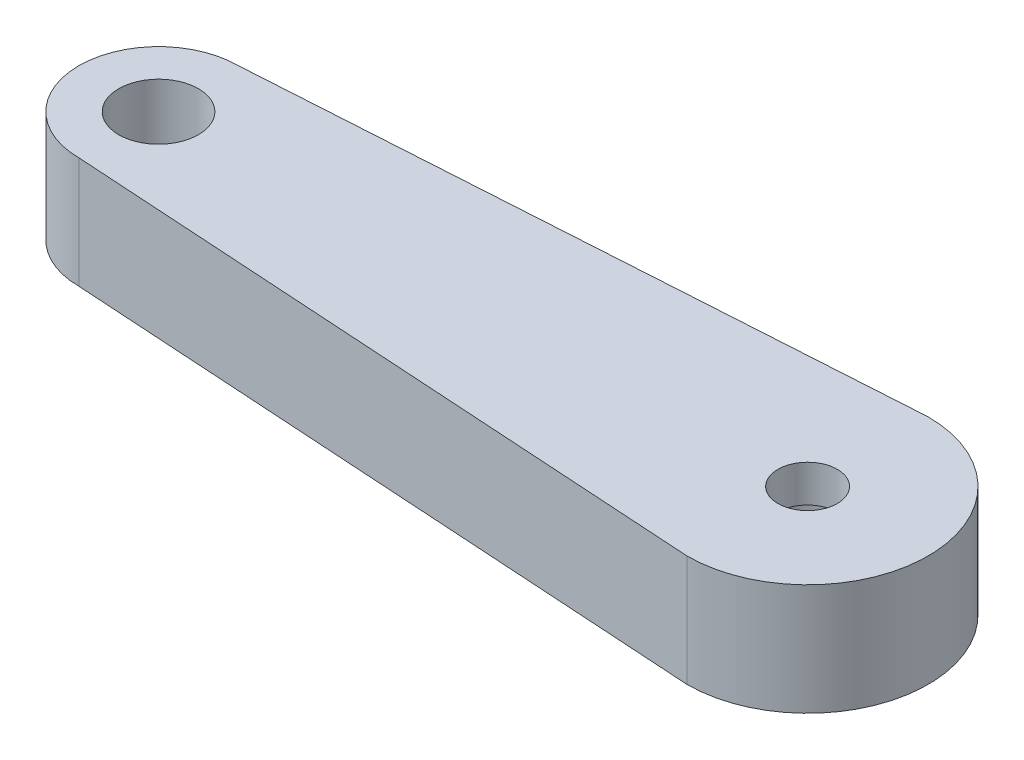
SolidWorks part; units mm, degrees
ref_plane "Front Plane" through (0, 0, 0) normal (0, 0, 1) x (1, 0, 0)
ref_plane "Top Plane" through (0, 0, 0) normal (0, 1, 0) x (1, 0, 0)
ref_plane "Right Plane" through (0, 0, 0) normal (1, 0, 0) x (0, 0, -1)
sketch "Sketch1" plane through (0, 0, 0) normal (0, 1, 0) x (1, 0, 0)
  line L0 (0, 0) -> (0, 6.5) construction
  line L1 (0, 0) -> (0, -6.5) construction
  line L2 (0, 0) -> (-35, 0) construction
  line L3 (-35, 0) -> (-35, 4.3) construction
  line L4 (-35, 0) -> (-35, -4.3) construction
  line L5 (-35, 4.3) -> (0, 6.5)
  line L6 (-35, -4.3) -> (0, -6.5)
  arc A1 (0, 6.5) -> (0, -6.5) centre (0, 0) cw
  arc A3 (-35, 4.3) -> (-35, -4.3) centre (-35, 0) ccw
  dimension "D4" = 4.3
  dimension "D5" = 4.3
  dimension "D1" = 6.5
  dimension "D2" = 6.5
  dimension "D3" = 35
extrude "Boss-Extrude1" add sketch "Sketch1" along normal blind 6 contours L5 A1 L6 A3
sketch "Sketch2" plane through (0, 0, 0) normal (0, 1, 0) x (1, 0, 0)
  circle A0 centre (-35, 0) radius 2.15
  dimension "D1" = 4.3
extrude "Cut-Extrude1" cut sketch "Sketch2" along normal blind 6
sketch "Sketch3" plane through (0, 0, 0) normal (0, 1, 0) x (1, 0, 0)
  circle A0 centre (0, 0) radius 2.95
  dimension "D1" = 5.9
extrude "Cut-Extrude2" cut sketch "Sketch3" along normal blind 4
sketch "Sketch4" plane through (0, 0, 0) normal (0, 1, 0) x (1, 0, 0)
  circle A0 centre (0, 0) radius 1.6
  dimension "D1" = 3.2
extrude "Cut-Extrude3" cut sketch "Sketch4" along normal blind 11
